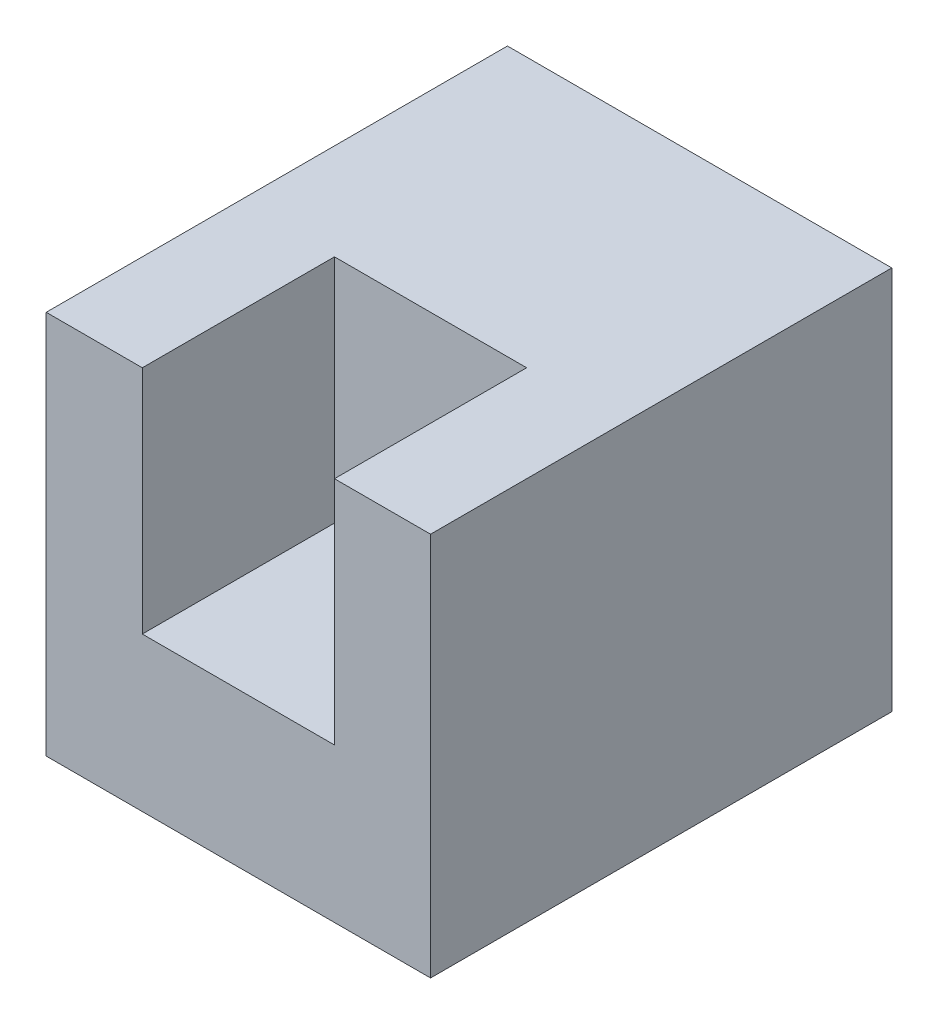
SolidWorks part; units mm, degrees
ref_plane "Front Plane" through (0, 0, 0) normal (0, 0, 1) x (1, 0, 0)
ref_plane "Top Plane" through (0, 0, 0) normal (0, 1, 0) x (1, 0, 0)
ref_plane "Right Plane" through (0, 0, 0) normal (1, 0, 0) x (0, 0, -1)
sketch "Sketch1" plane through (0, 0, 0) normal (0, 0, 1) x (1, 0, 0)
  line L1 (-6.35, 6.35) -> (6.35, 6.35)
  line L2 (-6.35, 6.35) -> (-6.35, -6.35)
  line L3 (-6.35, -6.35) -> (6.35, -6.35)
  line L4 (6.35, 6.35) -> (6.35, -6.35)
  line L5 (-6.35, 6.35) -> (6.35, -6.35) construction
  line L6 (-6.35, -6.35) -> (6.35, 6.35) construction
  point P0 (0, 0)
  dimension "D1" = 12.7
  dimension "D2" = 12.7
extrude "Boss-Extrude1" add sketch "Sketch1" along normal blind 15.24
sketch "Sketch2" plane through (0, 0, 15.24) normal (0, 0, 1) x (1, 0, 0)
  line L0 (6.35, 6.35) -> (-6.35, 6.35) construction
  line L1 (-3.175, 6.35) -> (3.175, 6.35)
  line L2 (-3.175, 6.35) -> (-3.175, -1.27)
  line L3 (-3.175, -1.27) -> (3.175, -1.27)
  line L4 (3.175, 6.35) -> (3.175, -1.27)
  point P6 (0, -1.27)
  dimension "D1" = 6.35
  dimension "D2" = 7.62
extrude "Cut-Extrude1" cut sketch "Sketch2" against normal blind 6.35
sketch "Sketch3" plane through (0, 0, 0) normal (0, 0, -1) x (-1, 0, 0)
  line L1 (-1.651, 1.651) -> (1.651, 1.651)
  line L2 (-1.651, 1.651) -> (-1.651, -1.651)
  line L3 (-1.651, -1.651) -> (1.651, -1.651)
  line L4 (1.651, 1.651) -> (1.651, -1.651)
  line L5 (-1.651, 1.651) -> (1.651, -1.651) construction
  line L6 (-1.651, -1.651) -> (1.651, 1.651) construction
  point P0 (0, 0)
  dimension "D1" = 4.6698
extrude "Cut-Extrude2" cut sketch "Sketch3" against normal blind 5.08
